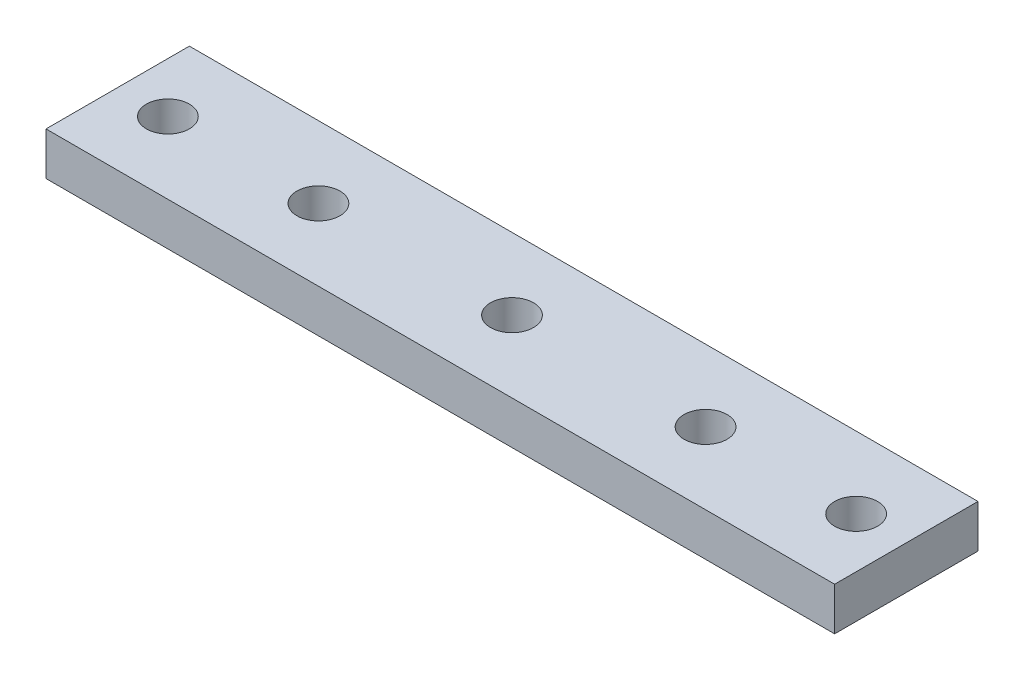
SolidWorks part; units mm, degrees
ref_plane "Plano frontal" through (0, 0, 0) normal (0, 0, 1) x (1, 0, 0)
ref_plane "Plano superior" through (0, 0, 0) normal (0, 1, 0) x (1, 0, 0)
ref_plane "Plano direito" through (0, 0, 0) normal (1, 0, 0) x (0, 0, -1)
sketch "Esboço1" plane through (0, 0, 0) normal (0, 1, 0) x (1, 0, 0)
  line L0 (0, 0) -> (0, 20)
  line L1 (0, 20) -> (110, 20)
  line L2 (110, 20) -> (110, 0)
  line L3 (110, 0) -> (0, 0)
  line L4 (55, 20) -> (55, 0) construction
  line L5 (110, 10) -> (0, 10) construction
  circle A0 centre (28, 10) radius 3
  circle A1 centre (82, 10) radius 3
  circle A2 centre (7, 10) radius 3
  circle A3 centre (103, 10) radius 3
  circle A4 centre (55, 10) radius 3
  point P13 (55, 10)
  dimension "D3" = 6
  dimension "D4" = 6
  dimension "D9" = 6
  dimension "D10" = 6
  dimension "D11" = 6
  dimension "D12" = 6
  dimension "D17" = 6
  dimension "D1" = 110
  dimension "D2" = 20
  dimension "D5" = 27
  dimension "D6" = 27
  dimension "D13" = 48
  dimension "D14" = 48
extrude "Ressalto-extrusão1" add sketch "Esboço1" along normal blind 6
